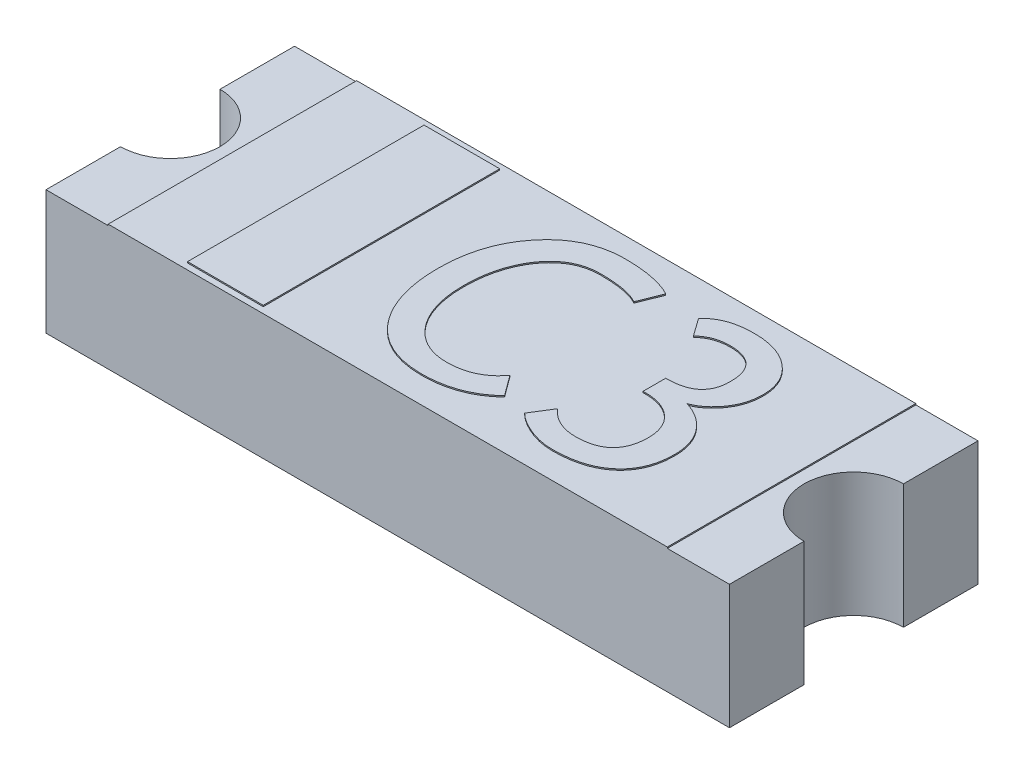
SolidWorks part; units mm, degrees
ref_plane "Front Plane" through (0, 0, 0) normal (0, 0, 1) x (1, 0, 0)
ref_plane "Top Plane" through (0, 0, 0) normal (0, 1, 0) x (1, 0, 0)
ref_plane "Right Plane" through (0, 0, 0) normal (1, 0, 0) x (0, 0, -1)
sketch "Sketch1" plane through (0, 0, 0) normal (0, 1, 0) x (1, 0, 0)
  line L1 (2.75, -1) -> (-2.75, -1)
  line L2 (2.75, -1) -> (2.75, 1)
  line L3 (2.75, 1) -> (-2.75, 1)
  line L4 (-2.75, -1) -> (-2.75, 1)
  line L5 (2.75, -1) -> (-2.75, 1) construction
  line L6 (2.75, 1) -> (-2.75, -1) construction
  point P0 (0, 0)
  dimension "D1" = 5.5
  dimension "D2" = 2
extrude "Boss-Extrude1" add sketch "Sketch1" along normal blind 1
sketch "Sketch2" plane through (0, 1, 0) normal (0, 1, 0) x (1, 0, 0)
  line L1 (2.25, -1) -> (-2.25, -1)
  line L2 (2.25, -1) -> (2.25, 1)
  line L3 (2.25, 1) -> (-2.25, 1)
  line L4 (-2.25, -1) -> (-2.25, 1)
  line L5 (2.25, -1) -> (-2.25, 1) construction
  line L6 (2.25, 1) -> (-2.25, -1) construction
  point P0 (0, 0)
  dimension "D1" = 4.5
  dimension "D2" = 2
extrude "Boss-Extrude2" add sketch "Sketch2" along normal blind 0.01
sketch "Sketch3" plane through (0, 1, 0) normal (0, 1, 0) x (1, 0, 0)
  line L0 (-2.75, 1) -> (-2.75, -1) construction
  line L1 (2.75, -1) -> (2.75, 1) construction
  circle A0 centre (-2.75, 0) radius 0.4
  circle A1 centre (2.75, 0) radius 0.4
  dimension "D1" = 0.8
  dimension "D2" = 0.8
extrude "Cut-Extrude1" cut sketch "Sketch3" against normal blind 3.01
sketch "Sketch4" plane through (0, 1.01, 0) normal (0, 1, 0) x (1, 0, 0)
  line L1 (-1.0504, -0.9514) -> (-1.6593, -0.9514)
  line L2 (-1.0504, -0.9514) -> (-1.0504, 0.9514)
  line L3 (-1.0504, 0.9514) -> (-1.6593, 0.9514)
  line L4 (-1.6593, -0.9514) -> (-1.6593, 0.9514)
  line L5 (-1.0504, -0.9514) -> (-1.6593, 0.9514) construction
  line L6 (-1.0504, 0.9514) -> (-1.6593, -0.9514) construction
  point P0 (-1.3548, 0)
extrude "Boss-Extrude3" add sketch "Sketch4" along normal blind 0.01
sketch "Sketch5" plane through (0, 1.01, 0) normal (0, 1, 0) x (1, 0, 0)
  text T0 "C3" font "Trebuchet MS" height in points 6
extrude "Boss-Extrude4" add sketch "Sketch5" along normal blind 0.01
